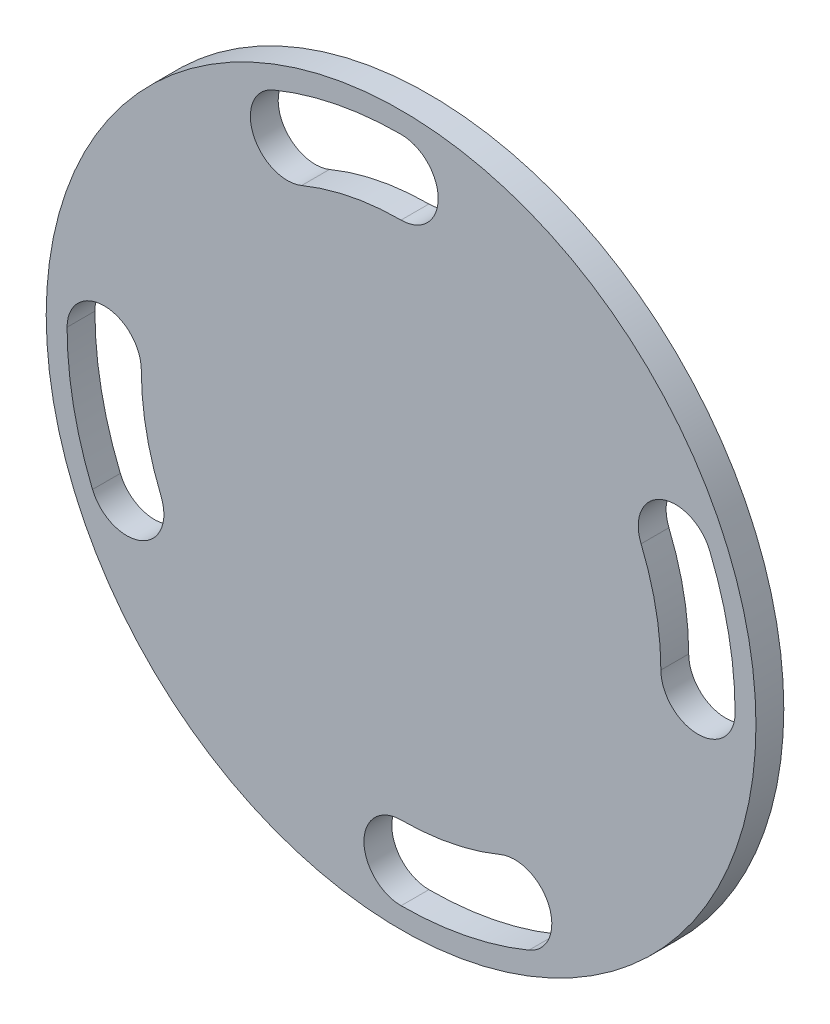
SolidWorks part; units mm, degrees
ref_plane "Front Plane" through (0, 0, 0) normal (0, 0, 1) x (1, 0, 0)
ref_plane "Top Plane" through (0, 0, 0) normal (0, 1, 0) x (1, 0, 0)
ref_plane "Right Plane" through (0, 0, 0) normal (1, 0, 0) x (0, 0, -1)
sketch "Sketch1" plane through (0, 0, 0) normal (0, 0, 1) x (1, 0, 0)
  circle A0 centre (0, 0) radius 7.65
  arc A2 (0, 5.6) -> (0, 7.2) centre (0, 6.4) ccw
  arc A5 (6.6519, 2.7553) -> (5.1737, 2.143) centre (5.9128, 2.4492) ccw
  arc A6 (5.6, 0) -> (7.2, 0) centre (6.4, 0) ccw
  arc A9 (2.7553, -6.6519) -> (2.143, -5.1737) centre (2.4492, -5.9128) ccw
  arc A10 (0, -5.6) -> (0, -7.2) centre (0, -6.4) ccw
  arc A13 (-6.6519, -2.7553) -> (-5.1737, -2.143) centre (-5.9128, -2.4492) ccw
  arc A14 (-5.6, 0) -> (-7.2, 0) centre (-6.4, 0) ccw
  arc A17 (-2.7553, 6.6519) -> (-2.143, 5.1737) centre (-2.4492, 5.9128) ccw
  circle A18 centre (-5.9128, 2.4492) radius 0.8 [skipped]
  circle A19 centre (-4.5255, 4.5255) radius 0.8 [skipped]
  circle A20 centre (2.4492, 5.9128) radius 0.8 [skipped]
  circle A21 centre (4.5255, 4.5255) radius 0.8 [skipped]
  circle A22 centre (5.9128, -2.4492) radius 0.8 [skipped]
  circle A23 centre (4.5255, -4.5255) radius 0.8 [skipped]
  circle A24 centre (-2.4492, -5.9128) radius 0.8 [skipped]
  circle A25 centre (-4.5255, -4.5255) radius 0.8 [skipped]
  arc A26 (0, 7.2) -> (-2.7553, 6.6519) centre (0, 0) ccw
  arc A27 (0, 5.6) -> (-2.143, 5.1737) centre (0, 0) ccw
  arc A28 (-7.2, 0) -> (-6.6519, -2.7553) centre (0, 0) ccw
  arc A29 (-5.6, 0) -> (-5.1737, -2.143) centre (0, 0) ccw
  arc A30 (0, -5.6) -> (2.143, -5.1737) centre (0, 0) ccw
  arc A31 (0, -7.2) -> (2.7553, -6.6519) centre (0, 0) ccw
  arc A32 (5.6, 0) -> (5.1737, 2.143) centre (0, 0) ccw
  arc A33 (7.2, 0) -> (6.6519, 2.7553) centre (0, 0) ccw
  point P15 (0, 0)
  dimension "D1" = 6.4
  dimension "D3" = 15.3
  dimension "D5" = 1.6
  dimension "D2" = 16
extrude "Boss-Extrude1" add sketch "Sketch1" along normal blind 0.6
